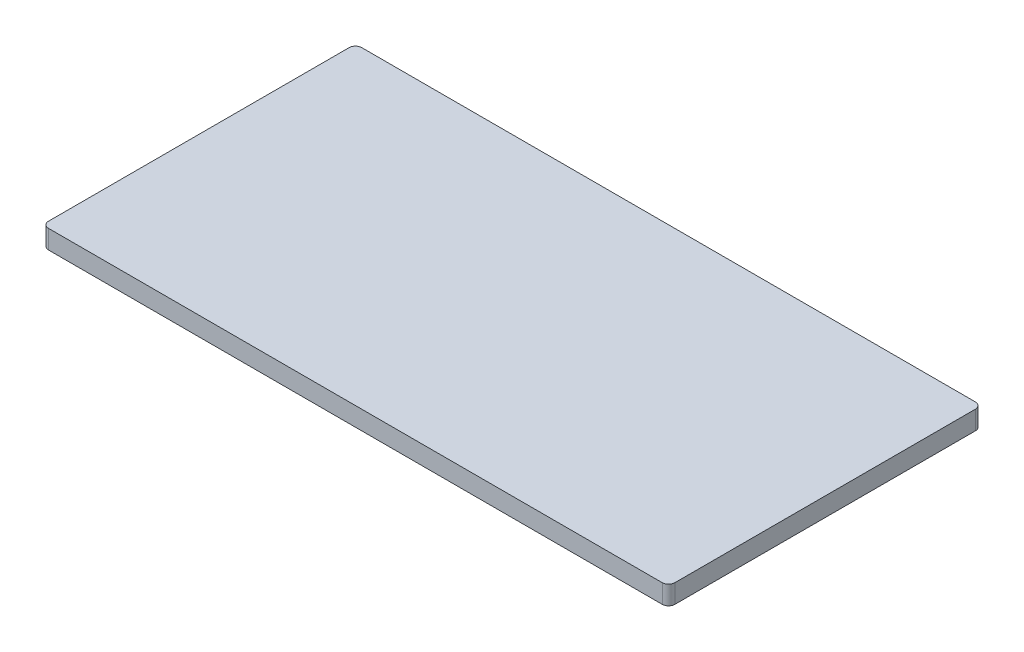
SolidWorks part; units mm, degrees
material "ABS"
ref_plane "Front Plane" through (0, 0, 0) normal (0, 0, 1) x (1, 0, 0)
ref_plane "Top Plane" through (0, 0, 0) normal (0, 1, 0) x (1, 0, 0)
ref_plane "Right Plane" through (0, 0, 0) normal (1, 0, 0) x (0, 0, -1)
sketch "Sketch1" plane through (0, 0, 0) normal (0, 1, 0) x (1, 0, 0)
  line L1 (0, 0) -> (100, 0)
  line L2 (0, 0) -> (0, 50)
  line L3 (0, 50) -> (100, 50)
  line L4 (100, 0) -> (100, 50)
  line L5 (0, 0) -> (100, 50) construction
  line L6 (0, 50) -> (100, 0) construction
  point P4 (50, 25)
  dimension "D1" = 50
  dimension "D2" = 100
extrude "Boss-Extrude1" add sketch "Sketch1" along normal blind 3
fillet "Fillet1" radius 1 4 edges at (0, 1.5, -50) (0, 1.5, 0) (100, 1.5, -50) (100, 1.5, 0)
